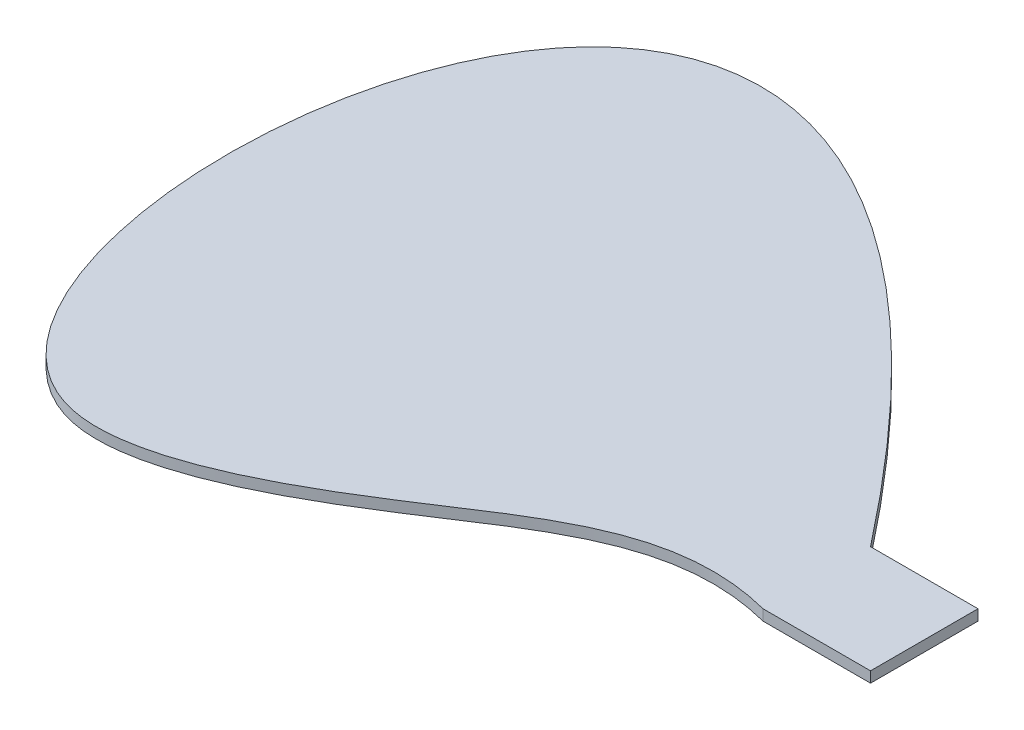
SolidWorks part; units mm, degrees
ref_plane "Front Plane" through (0, 0, 0) normal (0, 0, 1) x (1, 0, 0)
ref_plane "Top Plane" through (0, 0, 0) normal (0, 1, 0) x (1, 0, 0)
ref_plane "Right Plane" through (0, 0, 0) normal (1, 0, 0) x (0, 0, -1)
sketch "Sketch1" plane through (0, 0, 0) normal (0, 1, 0) x (1, 0, 0)
  line L1 (-2.5, 2.5) -> (2.5, 2.5)
  line L2 (-2.5, 2.5) -> (-2.5, -2.5) construction
  line L3 (-2.5, -2.5) -> (2.5, -2.5)
  line L4 (2.5, 2.5) -> (2.5, -2.5)
  line L5 (-2.5, 2.5) -> (2.5, -2.5) construction
  line L6 (-2.5, -2.5) -> (2.5, 2.5) construction
  spline S0 degree 3 poles (-2.5, -2.5) (-7.9545, -1.1042) (-14.0881, -6.5017) (-40.6313, -19.8708) (-34.68, 43.6579) (-2.5, 2.5) knots 0 0 0 0 0.200882 0.359947 1 1 1 1
  point P0 (0, 0)
  dimension "D1" = 5
  dimension "D2" = 5
extrude "Boss-Extrude2" add sketch "Sketch1" along normal mid plane 0.5
